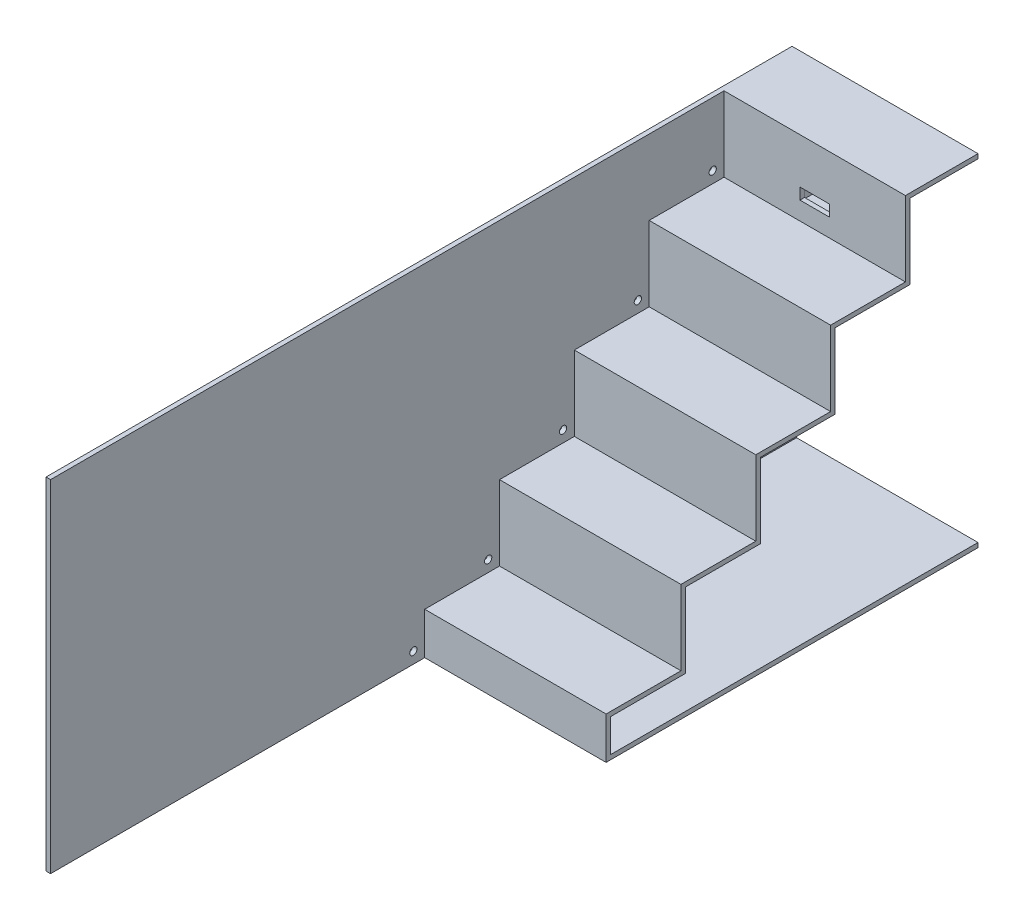
SolidWorks part; units mm, degrees
ref_plane "Front Plane" through (0, 0, 0) normal (0, 0, 1) x (1, 0, 0)
ref_plane "Top Plane" through (0, 0, 0) normal (0, 1, 0) x (1, 0, 0)
ref_plane "Right Plane" through (0, 0, 0) normal (1, 0, 0) x (0, 0, -1)
sketch "Sketch1" plane through (0, 0, 0) normal (1, 0, 0) x (0, 0, -1)
  line L0 (-23.9317, -26.5974) -> (-23.9317, 6.4026)
  line L1 (-25.9317, -24.5974) -> (-25.9317, 8.4026)
  line L3 (-25.9317, 8.4026) -> (7.0683, 8.4026)
  line L4 (-23.9317, 6.4026) -> (9.0683, 6.4026)
  line L6 (9.0683, 6.4026) -> (9.0683, 39.4026)
  line L7 (-23.9317, -26.5974) -> (-23.9317, 8.4026) construction
  line L8 (-25.9317, 6.4026) -> (9.0683, 6.4026) construction
  line L9 (7.0683, 8.4026) -> (7.0683, 41.4026)
  line L12 (-25.9317, 8.4026) -> (9.0683, 8.4026) construction
  line L13 (7.0683, 6.4026) -> (7.0683, 41.4026) construction
  line L14 (9.0683, 39.4026) -> (42.0683, 39.4026)
  line L16 (7.0683, 41.4026) -> (40.0683, 41.4026)
  line L17 (9.0683, 6.4026) -> (9.0683, 41.4026) construction
  line L18 (-23.9317, -26.5974) -> (-58.9317, -26.5974)
  line L19 (-25.9317, -24.5974) -> (-58.9317, -24.5974)
  line L20 (-58.9317, -24.5974) -> (-58.9317, -26.5974)
  line L22 (-25.9317, -26.5974) -> (-25.9317, 8.4026) construction
  line L23 (-23.9317, -24.5974) -> (-58.9317, -24.5974) construction
  line L24 (40.0683, 41.4026) -> (40.0683, 74.4026)
  line L26 (42.0683, 39.4026) -> (42.0683, 72.4026)
  line L27 (40.0683, 74.4026) -> (73.0683, 74.4026)
  line L28 (42.0683, 72.4026) -> (75.0683, 72.4026)
  line L30 (40.0683, 72.4026) -> (75.0683, 72.4026) construction
  line L31 (75.0683, 72.4026) -> (75.0683, 105.4026)
  line L32 (73.0683, 74.4026) -> (73.0683, 107.4026)
  line L34 (73.0683, 107.4026) -> (106.0683, 107.4026)
  line L35 (40.0683, 74.4026) -> (75.0683, 74.4026) construction
  line L36 (73.0683, 72.4026) -> (73.0683, 107.4026) construction
  line L37 (75.0683, 105.4026) -> (108.0683, 105.4026)
  line L39 (108.0683, 105.4026) -> (108.0683, 138.4026)
  line L40 (73.0683, 105.4026) -> (108.0683, 105.4026) construction
  line L41 (75.0683, 72.4026) -> (75.0683, 107.4026) construction
  line L42 (106.0683, 107.4026) -> (106.0683, 140.4026)
  line L44 (106.0683, 140.4026) -> (139.0683, 140.4026)
  line L45 (73.0683, 107.4026) -> (108.0683, 107.4026) construction
  line L46 (106.0683, 105.4026) -> (106.0683, 140.4026) construction
  line L47 (108.0683, 138.4026) -> (141.0683, 138.4026)
  line L49 (141.0683, 138.4026) -> (141.0683, 171.4026)
  line L50 (108.0683, 105.4026) -> (108.0683, 140.4026) construction
  line L51 (106.0683, 138.4026) -> (141.0683, 138.4026) construction
  line L52 (139.0683, 140.4026) -> (139.0683, 173.4026)
  line L54 (139.0683, 173.4026) -> (172.0683, 173.4026)
  line L55 (106.0683, 140.4026) -> (141.0683, 140.4026) construction
  line L56 (139.0683, 138.4026) -> (139.0683, 173.4026) construction
  line L57 (141.0683, 171.4026) -> (174.0683, 171.4026)
  line L59 (174.0683, 171.4026) -> (174.0683, 204.4026)
  line L60 (141.0683, 138.4026) -> (141.0683, 173.4026) construction
  line L61 (139.0683, 171.4026) -> (174.0683, 171.4026) construction
  line L62 (172.0683, 173.4026) -> (172.0683, 206.4026)
  line L64 (172.0683, 206.4026) -> (205.0683, 206.4026)
  line L65 (139.0683, 173.4026) -> (174.0683, 173.4026) construction
  line L66 (172.0683, 171.4026) -> (172.0683, 206.4026) construction
  line L67 (174.0683, 204.4026) -> (207.0683, 204.4026)
  line L69 (207.0683, 204.4026) -> (207.0683, 237.4026)
  line L70 (174.0683, 171.4026) -> (174.0683, 206.4026) construction
  line L71 (172.0683, 204.4026) -> (207.0683, 204.4026) construction
  line L72 (205.0683, 206.4026) -> (205.0683, 239.4026)
  line L74 (205.0683, 239.4026) -> (238.0683, 239.4026)
  line L75 (172.0683, 206.4026) -> (207.0683, 206.4026) construction
  line L76 (205.0683, 204.4026) -> (205.0683, 239.4026) construction
  line L77 (207.0683, 237.4026) -> (240.0683, 237.4026)
  line L79 (240.0683, 237.4026) -> (240.0683, 272.4026)
  line L80 (207.0683, 204.4026) -> (207.0683, 239.4026) construction
  line L81 (205.0683, 237.4026) -> (240.0683, 237.4026) construction
  line L82 (238.0683, 239.4026) -> (238.0683, 272.4026)
  line L83 (238.0683, 272.4026) -> (240.0683, 272.4026)
  line L85 (205.0683, 239.4026) -> (240.0683, 239.4026) construction
  line L86 (238.0683, 237.4026) -> (238.0683, 272.4026) construction
  point P12 (7.0683, 39.4026)
  point P13 (42.0683, 41.4026)
  point P20 (40.0683, 39.4026)
  dimension "D3" = 35
  dimension "D5" = 2
  dimension "D7" = 35
  dimension "D8" = 2
  dimension "D9" = 299
  dimension "D10" = 35
  dimension "D21" = 35
  dimension "D1" = 2
  dimension "D4" = 2
  dimension "D6" = 2
  dimension "D11" = 2
  dimension "D12" = 2
  dimension "D13" = 2
  dimension "D14" = 2
  dimension "D15" = 2
  dimension "D16" = 2
  dimension "D17" = 2
  dimension "D18" = 2
  dimension "D19" = 2
  dimension "D20" = 2
  dimension "D22" = 2
extrude "Boss-Extrude1" add sketch "Sketch1" along normal blind 80
sketch "Sketch3" plane through (0, 0, 0) normal (-1, 0, 0) x (0, 0, 1)
  line L1 (-240.0683, 272.4026) -> (58.9317, 272.4026)
  line L2 (-240.0683, 272.4026) -> (-240.0683, -26.5974)
  line L3 (-240.0683, -26.5974) -> (58.9317, -26.5974)
  line L4 (58.9317, 272.4026) -> (58.9317, -26.5974)
extrude "Boss-Extrude2" add sketch "Sketch3" along normal blind 2
sketch "Sketch4" plane through (0, -26.5974, 0) normal (0, -1, 0) x (1, 0, 0)
  line L0 (80, -207.0683) -> (80, -240.0683) construction
  line L1 (-2, 58.9317) -> (80, 58.9317)
  line L2 (-2, 58.9317) -> (-2, -240.0683)
  line L3 (-2, -240.0683) -> (80, -240.0683)
  line L4 (80, 58.9317) -> (80, -240.0683)
extrude "Boss-Extrude3" add sketch "Sketch4" along normal blind 2
sketch "Sketch6" plane through (-2, 0, 0) normal (-1, 0, 0) x (0, 0, 1)
  line L0 (-240.0683, 121.9026) -> (58.9317, 121.9026) construction
  line L1 (-240.0683, 272.4026) -> (-240.0683, -28.5974) construction
  line L2 (58.9317, -28.5974) -> (58.9317, 272.4026) construction
  line L4 (-240.0683, 121.9026) -> (58.9317, 121.9026)
  line L5 (-240.0683, 121.9026) -> (-240.0683, -28.5974)
  line L6 (-240.0683, -28.5974) -> (58.9317, -28.5974)
  line L7 (58.9317, 121.9026) -> (58.9317, -28.5974)
extrude "Cut-Extrude1" cut sketch "Sketch6" against normal up to surface (82 mm away) up to face at (80, 107.9526, -105.4183)
sketch "Sketch7" plane through (0, 0, 0) normal (1, 0, 0) x (0, 0, -1)
  line L0 (240.0683, 237.4026) -> (240.0683, 121.9026) construction
  line L1 (108.0683, 121.9026) -> (240.0683, 121.9026)
  line L2 (108.0683, 121.9026) -> (108.0683, 123.9026)
  line L3 (108.0683, 123.9026) -> (240.0683, 123.9026)
  line L4 (240.0683, 121.9026) -> (240.0683, 123.9026)
  dimension "D1" = 2
extrude "Boss-Extrude4" add sketch "Sketch7" along normal up to surface (80 mm away) up to face at (80, 190.5526, -173.0683)
sketch "Sketch8" plane through (0, 0, 0) normal (1, 0, 0) x (0, 0, -1)
  line L0 (106.0683, 140.4026) -> (106.0683, 121.9026) construction
  line L1 (-58.9317, 121.9026) -> (106.0683, 121.9026) construction
  line L2 (139.0683, 173.4026) -> (139.0683, 140.4026) construction
  line L3 (139.0683, 140.4026) -> (106.0683, 140.4026) construction
  line L4 (238.0683, 272.4026) -> (238.0683, 239.4026) construction
  line L5 (238.0683, 239.4026) -> (205.0683, 239.4026) construction
  line L6 (205.0683, 239.4026) -> (205.0683, 206.4026) construction
  line L7 (205.0683, 206.4026) -> (172.0683, 206.4026) construction
  line L8 (172.0683, 206.4026) -> (172.0683, 173.4026) construction
  line L9 (172.0683, 173.4026) -> (139.0683, 173.4026) construction
  circle A0 centre (101.0683, 126.9026) radius 1.6
  circle A1 centre (134.0683, 145.4026) radius 1.6
  circle A2 centre (167.0683, 178.4026) radius 1.6
  circle A3 centre (200.0683, 211.4026) radius 1.6
  circle A4 centre (233.0683, 244.4026) radius 1.6
  dimension "D1" = 3.2
  dimension "D4" = 3.2
  dimension "D7" = 3.2
  dimension "D8" = 3.2
  dimension "D9" = 3.2
  dimension "D2" = 5
  dimension "D3" = 5
  dimension "D5" = 5
  dimension "D6" = 5
  dimension "D10" = 5
  dimension "D11" = 5
  dimension "D12" = 5
  dimension "D13" = 5
  dimension "D14" = 5
  dimension "D15" = 5
extrude "Cut-Extrude2" cut sketch "Sketch8" against normal up to surface (2 mm away) up to face at (-2, 197.1526, -90.5683)
sketch "Sketch12" plane through (0, 0, -238.0683) normal (0, 0, 1) x (1, 0, 0)
  line L0 (40, 272.4026) -> (40, 239.4026) construction
  line L1 (80, 272.4026) -> (0, 272.4026) construction
  line L2 (80, 239.4026) -> (0, 239.4026) construction
  line L4 (33.5, 252.4026) -> (46.5, 252.4026)
  line L5 (33.5, 252.4026) -> (33.5, 247.4026)
  line L6 (33.5, 247.4026) -> (46.5, 247.4026)
  line L7 (46.5, 252.4026) -> (46.5, 247.4026)
  line L8 (33.5, 252.4026) -> (46.5, 247.4026) construction
  line L9 (33.5, 247.4026) -> (46.5, 252.4026) construction
  point P6 (40, 249.9026)
  dimension "D1" = 5
  dimension "D2" = 13
  dimension "D3" = 8
extrude "Cut-Extrude4" cut sketch "Sketch12" against normal up to surface (2 mm away) up to face at (39.5, 188.9026, -240.0683)
sketch "Sketch14" plane through (0, 0, -238.0683) normal (0, 0, 1) x (1, 0, 0)
  line L0 (40, 272.4026) -> (40, 239.4026) construction
  line L1 (80, 272.4026) -> (0, 272.4026) construction
  line L2 (80, 239.4026) -> (0, 239.4026) construction
  line L3 (33.5, 249.9026) -> (46.5, 249.9026) construction
  line L4 (33.5, 252.4026) -> (33.5, 247.4026) construction
  line L5 (46.5, 247.4026) -> (46.5, 252.4026) construction
  line L6 (31, 255.4026) -> (49, 255.4026)
  line L7 (33, 253.4026) -> (47, 253.4026)
  line L8 (33, 253.4026) -> (33, 246.4026)
  line L9 (33, 246.4026) -> (47, 246.4026)
  line L10 (47, 253.4026) -> (47, 246.4026)
  line L11 (33, 253.4026) -> (47, 246.4026) construction
  line L12 (33, 246.4026) -> (47, 253.4026) construction
  line L13 (49, 255.4026) -> (49, 244.4026)
  line L14 (31, 244.4026) -> (49, 244.4026)
  line L15 (31, 255.4026) -> (31, 244.4026)
  point P12 (40, 249.9026)
  dimension "D1" = 14
  dimension "D2" = 7
  dimension "D3" = 2
extrude "Boss-Extrude5" add sketch "Sketch14" against normal blind 10
sketch "Sketch15" plane through (0, 0, -240.0683) normal (0, 0, -1) x (-1, 0, 0)
  line L0 (-80, 272.4026) -> (2, 272.4026) construction
  line L1 (-80, 272.4026) -> (2, 272.4026)
  line L2 (2, 272.4026) -> (2, 121.9026) construction
  line L3 (2, 272.4026) -> (2, 121.9026)
  line L4 (-80, 270.4026) -> (0, 270.4026)
  line L5 (0, 270.4026) -> (0, 121.9026)
  line L6 (-80, 272.4026) -> (-80, 270.4026)
  line L7 (2, 121.9026) -> (0, 121.9026)
  dimension "D1" = 2
extrude "Boss-Extrude6" add sketch "Sketch15" along normal blind 30
sketch "Sketch16" plane through (0, 0, -240.0683) normal (0, 0, -1) x (-1, 0, 0)
  line L4 (0, 121.9026) -> (0, 123.9026)
  line L5 (0, 123.9026) -> (-80, 123.9026)
  line L6 (-80, 123.9026) -> (-80, 121.9026)
  line L7 (-80, 121.9026) -> (0, 121.9026)
  line L8 (0, 121.9026) -> (0, 123.9026)
  line L9 (0, 123.9026) -> (-80, 123.9026)
  line L10 (-80, 123.9026) -> (-80, 121.9026)
  line L11 (-80, 121.9026) -> (0, 121.9026)
  dimension "D1" = 0
extrude "Boss-Extrude7" add sketch "Sketch16" along normal blind 30
